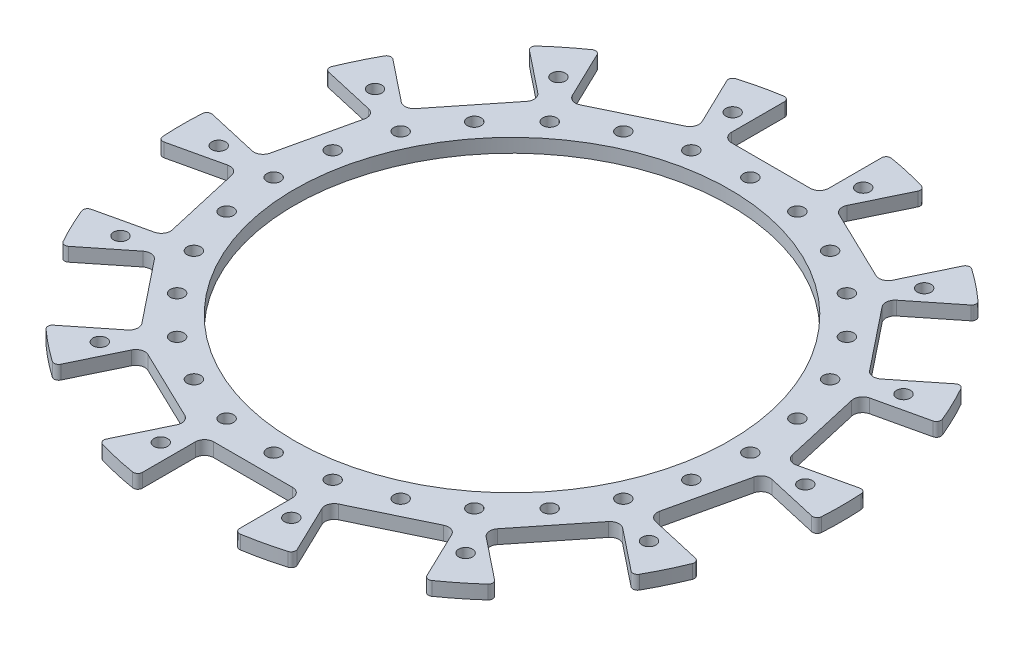
SolidWorks part; units mm, degrees
material "Thornel Mat VMA"
ref_plane "前视基准面" through (0, 0, 0) normal (0, 0, 1) x (1, 0, 0)
ref_plane "上视基准面" through (0, 0, 0) normal (0, 1, 0) x (1, 0, 0)
ref_plane "右视基准面" through (0, 0, 0) normal (1, 0, 0) x (0, 0, -1)
sketch "草图1" plane through (0, 0, 0) normal (0, 1, 0) x (1, 0, 0)
  line L0 (0, 0) -> (0, -67) construction
  line L1 (13, -67) -> (-13, -67) construction
  line L2 (-13, -68.5) -> (-13, -65.5)
  line L3 (0, -67) -> (0, -69.5129) construction
  line L4 (-10.1, -69.5129) -> (10.1, -69.5129) construction
  line L5 (-13, -68.5) -> (-10.6, -68.5)
  line L6 (-10.6, -68.5) -> (-10.6, -71.2154)
  line L7 (-13, -65.5) -> (-10.6, -65.5)
  line L8 (-10.6, -65.5) -> (-10.6, -56.5)
  line L9 (-10.6, -56.5) -> (10.6, -56.5)
  line L10 (10.6, -68.5) -> (10.6, -71.2154)
  line L11 (13, -68.5) -> (10.6, -68.5)
  line L12 (13, -68.5) -> (13, -65.5)
  line L13 (13, -65.5) -> (10.6, -65.5)
  line L14 (10.6, -65.5) -> (10.6, -56.5)
  line L15 (-34.0647, -46.3056) -> (-14.9642, -55.5039)
  line L16 (-37.9697, -54.4143) -> (-34.0647, -46.3056)
  line L17 (-40.132, -53.373) -> (-37.9697, -54.4143)
  line L18 (-41.4336, -56.0759) -> (-40.132, -53.373)
  line L19 (-41.4336, -56.0759) -> (-39.2713, -57.1172)
  line L20 (-39.2713, -57.1172) -> (-40.4495, -59.5637)
  line L21 (-20.1708, -66.3155) -> (-21.349, -68.7621)
  line L22 (-18.0084, -67.3569) -> (-20.1708, -66.3155)
  line L23 (-18.0084, -67.3569) -> (-16.7068, -64.6539)
  line L24 (-16.7068, -64.6539) -> (-18.8691, -63.6126)
  line L25 (-18.8691, -63.6126) -> (-14.9642, -55.5039)
  line L26 (-50.7825, -26.9398) -> (-37.5645, -43.5146)
  line L27 (-57.819, -32.5512) -> (-50.7825, -26.9398)
  line L28 (-59.3153, -30.6748) -> (-57.819, -32.5512)
  line L29 (-61.6608, -32.5452) -> (-59.3153, -30.6748)
  line L30 (-61.6608, -32.5452) -> (-60.1644, -34.4216)
  line L31 (-60.1644, -34.4216) -> (-62.2875, -36.1147)
  line L32 (-46.9465, -50.9965) -> (-49.0695, -52.6895)
  line L33 (-45.4501, -52.8729) -> (-46.9465, -50.9965)
  line L34 (-45.4501, -52.8729) -> (-43.1046, -51.0024)
  line L35 (-43.1046, -51.0024) -> (-44.601, -49.126)
  line L36 (-44.601, -49.126) -> (-37.5645, -43.5146)
  line L37 (-57.4421, -2.2382) -> (-52.7247, -22.9067)
  line L38 (-66.2165, -4.2409) -> (-57.4421, -2.2382)
  line L39 (-66.7506, -1.9011) -> (-66.2165, -4.2409)
  line L40 (-69.6753, -2.5686) -> (-66.7506, -1.9011)
  line L41 (-69.6753, -2.5686) -> (-69.1413, -4.9084)
  line L42 (-69.1413, -4.9084) -> (-71.7886, -5.5127)
  line L43 (-64.4238, -25.5769) -> (-67.0712, -26.1812)
  line L44 (-63.8898, -27.9167) -> (-64.4238, -25.5769)
  line L45 (-63.8898, -27.9167) -> (-60.965, -27.2492)
  line L46 (-60.965, -27.2492) -> (-61.4991, -24.9094)
  line L47 (-61.4991, -24.9094) -> (-52.7247, -22.9067)
  line L48 (-52.7247, 22.9067) -> (-57.4421, 2.2382)
  line L49 (-61.4991, 24.9094) -> (-52.7247, 22.9067)
  line L50 (-60.965, 27.2492) -> (-61.4991, 24.9094)
  line L51 (-63.8898, 27.9167) -> (-60.965, 27.2492)
  line L52 (-63.8898, 27.9167) -> (-64.4238, 25.5769)
  line L53 (-64.4238, 25.5769) -> (-67.0712, 26.1812)
  line L54 (-69.1413, 4.9084) -> (-71.7886, 5.5127)
  line L55 (-69.6753, 2.5686) -> (-69.1413, 4.9084)
  line L56 (-69.6753, 2.5686) -> (-66.7506, 1.9011)
  line L57 (-66.7506, 1.9011) -> (-66.2165, 4.2409)
  line L58 (-66.2165, 4.2409) -> (-57.4421, 2.2382)
  line L59 (-37.5645, 43.5146) -> (-50.7825, 26.9398)
  line L60 (-44.601, 49.126) -> (-37.5645, 43.5146)
  line L61 (-43.1046, 51.0024) -> (-44.601, 49.126)
  line L62 (-45.4501, 52.8729) -> (-43.1046, 51.0024)
  line L63 (-45.4501, 52.8729) -> (-46.9465, 50.9965)
  line L64 (-46.9465, 50.9965) -> (-49.0695, 52.6895)
  line L65 (-60.1644, 34.4216) -> (-62.2875, 36.1147)
  line L66 (-61.6608, 32.5452) -> (-60.1644, 34.4216)
  line L67 (-61.6608, 32.5452) -> (-59.3153, 30.6748)
  line L68 (-59.3153, 30.6748) -> (-57.819, 32.5512)
  line L69 (-57.819, 32.5512) -> (-50.7825, 26.9398)
  line L70 (-14.9642, 55.5039) -> (-34.0647, 46.3056)
  line L71 (-18.8691, 63.6126) -> (-14.9642, 55.5039)
  line L72 (-16.7068, 64.6539) -> (-18.8691, 63.6126)
  line L73 (-18.0084, 67.3569) -> (-16.7068, 64.6539)
  line L74 (-18.0084, 67.3569) -> (-20.1708, 66.3155)
  line L75 (-20.1708, 66.3155) -> (-21.349, 68.7621)
  line L76 (-39.2713, 57.1172) -> (-40.4495, 59.5637)
  line L77 (-41.4336, 56.0759) -> (-39.2713, 57.1172)
  line L78 (-41.4336, 56.0759) -> (-40.132, 53.373)
  line L79 (-40.132, 53.373) -> (-37.9697, 54.4143)
  line L80 (-37.9697, 54.4143) -> (-34.0647, 46.3056)
  line L81 (10.6, 56.5) -> (-10.6, 56.5)
  line L82 (10.6, 65.5) -> (10.6, 56.5)
  line L83 (13, 65.5) -> (10.6, 65.5)
  line L84 (13, 68.5) -> (13, 65.5)
  line L85 (13, 68.5) -> (10.6, 68.5)
  line L86 (10.6, 68.5) -> (10.6, 71.2154)
  line L87 (-10.6, 68.5) -> (-10.6, 71.2154)
  line L88 (-13, 68.5) -> (-10.6, 68.5)
  line L89 (-13, 68.5) -> (-13, 65.5)
  line L90 (-13, 65.5) -> (-10.6, 65.5)
  line L91 (-10.6, 65.5) -> (-10.6, 56.5)
  line L92 (34.0647, 46.3056) -> (14.9642, 55.5039)
  line L93 (37.9697, 54.4143) -> (34.0647, 46.3056)
  line L94 (40.132, 53.373) -> (37.9697, 54.4143)
  line L95 (41.4336, 56.0759) -> (40.132, 53.373)
  line L96 (41.4336, 56.0759) -> (39.2713, 57.1172)
  line L97 (39.2713, 57.1172) -> (40.4495, 59.5637)
  line L98 (20.1708, 66.3155) -> (21.349, 68.7621)
  line L99 (18.0084, 67.3569) -> (20.1708, 66.3155)
  line L100 (18.0084, 67.3569) -> (16.7068, 64.6539)
  line L101 (16.7068, 64.6539) -> (18.8691, 63.6126)
  line L102 (18.8691, 63.6126) -> (14.9642, 55.5039)
  line L103 (50.7825, 26.9398) -> (37.5645, 43.5146)
  line L104 (57.819, 32.5512) -> (50.7825, 26.9398)
  line L105 (59.3153, 30.6748) -> (57.819, 32.5512)
  line L106 (61.6608, 32.5452) -> (59.3153, 30.6748)
  line L107 (61.6608, 32.5452) -> (60.1644, 34.4216)
  line L108 (60.1644, 34.4216) -> (62.2875, 36.1147)
  line L109 (46.9465, 50.9965) -> (49.0695, 52.6895)
  line L110 (45.4501, 52.8729) -> (46.9465, 50.9965)
  line L111 (45.4501, 52.8729) -> (43.1046, 51.0024)
  line L112 (43.1046, 51.0024) -> (44.601, 49.126)
  line L113 (44.601, 49.126) -> (37.5645, 43.5146)
  line L114 (57.4421, 2.2382) -> (52.7247, 22.9067)
  line L115 (66.2165, 4.2409) -> (57.4421, 2.2382)
  line L116 (66.7506, 1.9011) -> (66.2165, 4.2409)
  line L117 (69.6753, 2.5686) -> (66.7506, 1.9011)
  line L118 (69.6753, 2.5686) -> (69.1413, 4.9084)
  line L119 (69.1413, 4.9084) -> (71.7886, 5.5127)
  line L120 (64.4238, 25.5769) -> (67.0712, 26.1812)
  line L121 (63.8898, 27.9167) -> (64.4238, 25.5769)
  line L122 (63.8898, 27.9167) -> (60.965, 27.2492)
  line L123 (60.965, 27.2492) -> (61.4991, 24.9094)
  line L124 (61.4991, 24.9094) -> (52.7247, 22.9067)
  line L125 (52.7247, -22.9067) -> (57.4421, -2.2382)
  line L126 (61.4991, -24.9094) -> (52.7247, -22.9067)
  line L127 (60.965, -27.2492) -> (61.4991, -24.9094)
  line L128 (63.8898, -27.9167) -> (60.965, -27.2492)
  line L129 (63.8898, -27.9167) -> (64.4238, -25.5769)
  line L130 (64.4238, -25.5769) -> (67.0712, -26.1812)
  line L131 (69.1413, -4.9084) -> (71.7886, -5.5127)
  line L132 (69.6753, -2.5686) -> (69.1413, -4.9084)
  line L133 (69.6753, -2.5686) -> (66.7506, -1.9011)
  line L134 (66.7506, -1.9011) -> (66.2165, -4.2409)
  line L135 (66.2165, -4.2409) -> (57.4421, -2.2382)
  line L136 (37.5645, -43.5146) -> (50.7825, -26.9398)
  line L137 (44.601, -49.126) -> (37.5645, -43.5146)
  line L138 (43.1046, -51.0024) -> (44.601, -49.126)
  line L139 (45.4501, -52.8729) -> (43.1046, -51.0024)
  line L140 (45.4501, -52.8729) -> (46.9465, -50.9965)
  line L141 (46.9465, -50.9965) -> (49.0695, -52.6895)
  line L142 (60.1644, -34.4216) -> (62.2875, -36.1147)
  line L143 (61.6608, -32.5452) -> (60.1644, -34.4216)
  line L144 (61.6608, -32.5452) -> (59.3153, -30.6748)
  line L145 (59.3153, -30.6748) -> (57.819, -32.5512)
  line L146 (57.819, -32.5512) -> (50.7825, -26.9398)
  line L147 (14.9642, -55.5039) -> (34.0647, -46.3056)
  line L148 (18.8691, -63.6126) -> (14.9642, -55.5039)
  line L149 (16.7068, -64.6539) -> (18.8691, -63.6126)
  line L150 (18.0084, -67.3569) -> (16.7068, -64.6539)
  line L151 (18.0084, -67.3569) -> (20.1708, -66.3155)
  line L152 (20.1708, -66.3155) -> (21.349, -68.7621)
  line L153 (39.2713, -57.1172) -> (40.4495, -59.5637)
  line L154 (41.4336, -56.0759) -> (39.2713, -57.1172)
  line L155 (41.4336, -56.0759) -> (40.132, -53.373)
  line L156 (40.132, -53.373) -> (37.9697, -54.4143)
  line L157 (37.9697, -54.4143) -> (34.0647, -46.3056)
  line L158 (-10.6, -65.5) -> (-10.6, -68.5)
  line L159 (10.6, -65.5) -> (10.6, -68.5)
  line L160 (-18.8691, -63.6126) -> (-20.1708, -66.3155)
  line L161 (-37.9697, -54.4143) -> (-39.2713, -57.1172)
  line L162 (-44.601, -49.126) -> (-46.9465, -50.9965)
  line L163 (-57.819, -32.5512) -> (-60.1644, -34.4216)
  line L164 (-61.4991, -24.9094) -> (-64.4238, -25.5769)
  line L165 (-66.2165, -4.2409) -> (-69.1413, -4.9084)
  line L166 (-66.2165, 4.2409) -> (-69.1413, 4.9084)
  line L167 (-61.4991, 24.9094) -> (-64.4238, 25.5769)
  line L168 (-57.819, 32.5512) -> (-60.1644, 34.4216)
  line L169 (-44.601, 49.126) -> (-46.9465, 50.9965)
  line L170 (-37.9697, 54.4143) -> (-39.2713, 57.1172)
  line L171 (-18.8691, 63.6126) -> (-20.1708, 66.3155)
  line L172 (-10.6, 65.5) -> (-10.6, 68.5)
  line L173 (10.6, 65.5) -> (10.6, 68.5)
  line L174 (18.8691, 63.6126) -> (20.1708, 66.3155)
  line L175 (37.9697, 54.4143) -> (39.2713, 57.1172)
  line L176 (44.601, 49.126) -> (46.9465, 50.9965)
  line L177 (57.819, 32.5512) -> (60.1644, 34.4216)
  line L178 (61.4991, 24.9094) -> (64.4238, 25.5769)
  line L179 (66.2165, 4.2409) -> (69.1413, 4.9084)
  line L180 (66.2165, -4.2409) -> (69.1413, -4.9084)
  line L181 (61.4991, -24.9094) -> (64.4238, -25.5769)
  line L182 (57.819, -32.5512) -> (60.1644, -34.4216)
  line L183 (44.601, -49.126) -> (46.9465, -50.9965)
  line L184 (37.9697, -54.4143) -> (39.2713, -57.1172)
  line L185 (18.8691, -63.6126) -> (20.1708, -66.3155)
  circle A0 centre (0, 0) radius 67 construction
  circle A1 centre (0, 0) radius 72
  point P7 (0, -67)
  point P10 (-13, -67)
  point P21 (0, -69.5129)
  point P26 (0, -56.5)
  point P185 (0, 0)
  point P237 (0, 0)
  dimension "D1" = 134
  dimension "D5" = 144
  dimension "D2" = 26
  dimension "D3" = 3
  dimension "D4" = 20.2
  dimension "D6" = 0.5
  dimension "D7" = 10.5
  dimension "D8" = 14
  dimension "D9" = 14
extrude "凸台-拉伸1" add sketch "草图1" along normal blind 3 contours L10 A1 L152 L151 L150 L149 L148 L147 L157 L156 L155 L154 L153 L141 L140 L139 L138 L137 L136 L146 L145 L144 L143 L142 L130 L129 L128 L127 L126 L125 L135 L134 L133 L132 L131 L119 L118 L117 L116 L115 L114 L124 L123 L122 L121 L120 L108 | L161 L17 L18 L19 | L163 L28 L29 L30 | L35 L162 L33 L34 | L46 L164 L44 L45 | L24 L160 L22 L23 | L158 L7 L2 L5 | L185 L149 L150 L151 | L13 L159 L11 L12 | L156 L184 L154 L155 | L183 L138 L139 L140 | L145 L182 L143 L144 | L181 L127 L128 L129 | L134 L180 L132 L133 | L179 L116 L117 L118 | L177 L105 L106 L107 | L123 L178 L121 L122 | L112 L176 L110 L111 | L175 L94 L95 L96 | L101 L174 L99 L100 | L173 L83 L84 L85 | L171 L72 L73 L74 | L90 L172 L88 L89 | L169 L61 L62 L63 | L79 L170 L77 L78 | L167 L50 L51 L52 | L68 L168 L66 L67 | L165 L39 L40 L41 | L57 L166 L55 L56
fillet "圆角1" radius 2 28 edges at (50.7825, 1.5, 26.9398) (57.4421, 1.5, 2.2382) (52.7247, 1.5, -22.9067) (37.5645, 1.5, -43.5146) (14.9642, 1.5, -55.5039) (-10.6, 1.5, -56.5) (-34.0647, 1.5, -46.3056) (-50.7825, 1.5, -26.9398) (-57.4421, 1.5, -2.2382) (-52.7247, 1.5, 22.9067) (-37.5645, 1.5, 43.5146) (-14.9642, 1.5, 55.5039) (-34.0647, 1.5, 46.3056) (-50.7825, 1.5, 26.9398) (-57.4421, 1.5, 2.2382) (-52.7247, 1.5, -22.9067) (-37.5645, 1.5, -43.5146) (-14.9642, 1.5, -55.5039) (10.6, 1.5, -56.5) (34.0647, 1.5, -46.3056) (57.4421, 1.5, -2.2382) (50.7825, 1.5, -26.9398) (52.7247, 1.5, 22.9067) (37.5645, 1.5, 43.5146) (34.0647, 1.5, 46.3056) (14.9642, 1.5, 55.5039) (10.6, 1.5, 56.5) (-10.6, 1.5, 56.5)
fillet "圆角2" radius 1 28 edges at (-21.349, 1.5, -68.7621) (40.4495, 1.5, 59.5637) (10.6, 1.5, 71.2154) (10.6, 1.5, -71.2154) (-49.0695, 1.5, -52.6895) (62.2875, 1.5, 36.1147) (-67.0712, 1.5, -26.1812) (71.7886, 1.5, 5.5127) (-71.7886, 1.5, 5.5127) (67.0712, 1.5, -26.1812) (-62.2875, 1.5, 36.1147) (49.0695, 1.5, -52.6895) (-40.4495, 1.5, 59.5637) (21.349, 1.5, -68.7621) (-10.6, 1.5, 71.2154) (-10.6, 1.5, -71.2154) (-40.4495, 1.5, -59.5637) (21.349, 1.5, 68.7621) (-62.2875, 1.5, -36.1147) (49.0695, 1.5, 52.6895) (-71.7886, 1.5, -5.5127) (67.0712, 1.5, 26.1812) (-67.0712, 1.5, 26.1812) (71.7886, 1.5, -5.5127) (-21.349, 1.5, 68.7621) (40.4495, 1.5, -59.5637) (-49.0695, 1.5, 52.6895) (62.2875, 1.5, -36.1147)
sketch "草图2" plane through (0, 0, 0) normal (0, 1, 0) x (1, 0, 0)
  line L0 (64, 0) -> (0, 0) construction
  circle A0 centre (64, 0) radius 1.5
  circle A1 centre (57.662, -27.7686) radius 1.5
  circle A2 centre (39.9033, -50.0372) radius 1.5
  circle A3 centre (14.2413, -62.3954) radius 1.5
  circle A4 centre (-14.2413, -62.3954) radius 1.5
  circle A5 centre (-39.9033, -50.0372) radius 1.5
  circle A6 centre (-57.662, -27.7686) radius 1.5
  circle A7 centre (-64, 0) radius 1.5
  circle A8 centre (-57.662, 27.7686) radius 1.5
  circle A9 centre (-39.9033, 50.0372) radius 1.5
  circle A10 centre (-14.2413, 62.3954) radius 1.5
  circle A11 centre (14.2413, 62.3954) radius 1.5
  circle A12 centre (39.9033, 50.0372) radius 1.5
  circle A13 centre (57.662, 27.7686) radius 1.5
  point P32 (0, 0)
  dimension "D1" = 3
  dimension "D2" = 64
  dimension "D3" = 14
extrude "切除-拉伸1" cut sketch "草图2" along normal blind 11
sketch "草图3" plane through (0, 0, 0) normal (0, 1, 0) x (1, 0, 0)
  line L0 (0, -56.5) -> (0, -52.5) construction
  line L1 (-8.6, -56.5) -> (8.6, -56.5) construction
  circle A0 centre (0, 0) radius 9
  circle A1 centre (0, 0) radius 28
  circle A2 centre (0, 0) radius 52.5
  dimension "D1" = 18
  dimension "D2" = 56
  dimension "D3" = 4
extrude "切除-拉伸2" cut sketch "草图3" along normal blind 11 contours A0 | A2 A1 | A1 A0
sketch "草图9" plane through (0, 3, 0) normal (0, 1, 0) x (1, 0, 0)
  circle A0 centre (0, 0) radius 52.5
  circle A1 centre (0, 0) radius 47.5
  dimension "D1" = 105
  dimension "D2" = 95
extrude "凸台-拉伸2" add sketch "草图9" against normal blind 3
sketch "草图10" plane through (0, 3, 0) normal (0, 1, 0) x (1, 0, 0)
  circle A0 centre (0, 0) radius 52 construction
  circle A1 centre (0, 52) radius 1.5
  circle A2 centre (11.5711, 50.6963) radius 1.5
  circle A3 centre (22.562, 46.8504) radius 1.5
  circle A4 centre (32.4215, 40.6552) radius 1.5
  circle A5 centre (40.6552, 32.4215) radius 1.5
  circle A6 centre (46.8504, 22.562) radius 1.5
  circle A7 centre (50.6963, 11.5711) radius 1.5
  circle A8 centre (52, 0) radius 1.5
  circle A9 centre (50.6963, -11.5711) radius 1.5
  circle A10 centre (46.8504, -22.562) radius 1.5
  circle A11 centre (40.6552, -32.4215) radius 1.5
  circle A12 centre (32.4215, -40.6552) radius 1.5
  circle A13 centre (22.562, -46.8504) radius 1.5
  circle A14 centre (11.5711, -50.6963) radius 1.5
  circle A15 centre (0, -52) radius 1.5
  circle A16 centre (-11.5711, -50.6963) radius 1.5
  circle A17 centre (-22.562, -46.8504) radius 1.5
  circle A18 centre (-32.4215, -40.6552) radius 1.5
  circle A19 centre (-40.6552, -32.4215) radius 1.5
  circle A20 centre (-46.8504, -22.562) radius 1.5
  circle A21 centre (-50.6963, -11.5711) radius 1.5
  circle A22 centre (-52, 0) radius 1.5
  circle A23 centre (-50.6963, 11.5711) radius 1.5
  circle A24 centre (-46.8504, 22.562) radius 1.5
  circle A25 centre (-40.6552, 32.4215) radius 1.5
  circle A26 centre (-32.4215, 40.6552) radius 1.5
  circle A27 centre (-22.562, 46.8504) radius 1.5
  circle A28 centre (-11.5711, 50.6963) radius 1.5
  point P62 (0, 0)
  dimension "D1" = 104
  dimension "D2" = 3
  dimension "D3" = 28
extrude "切除-拉伸3" cut sketch "草图10" against normal blind 3
